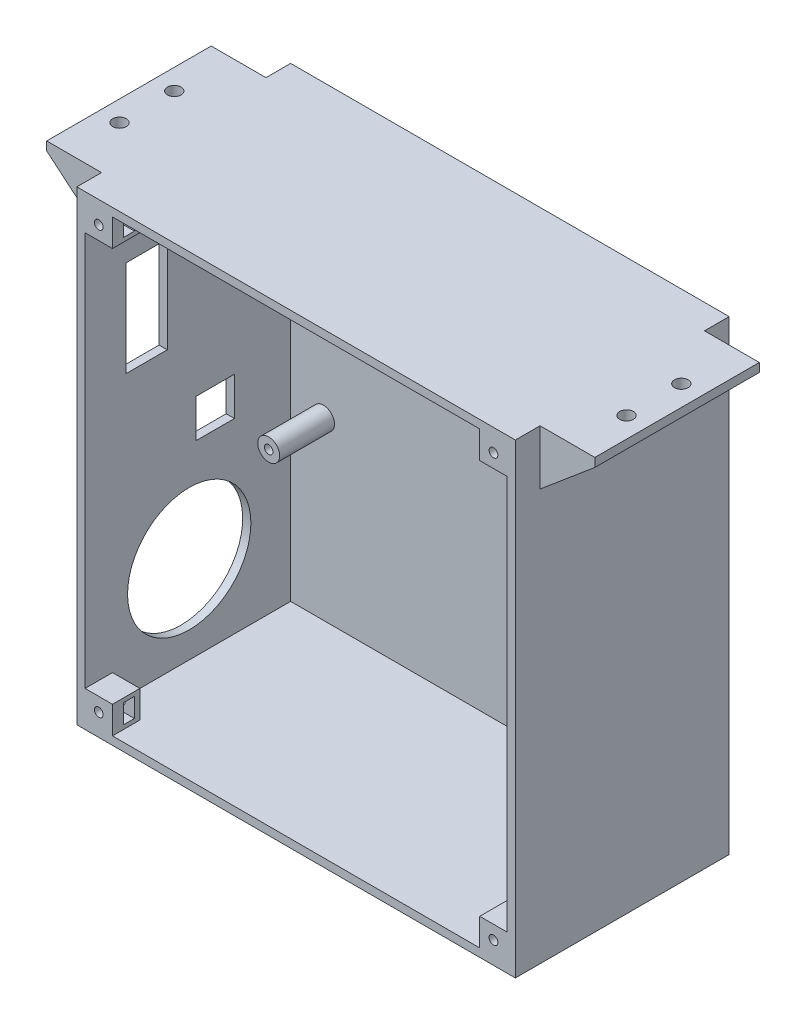
SolidWorks part; units mm, degrees
ref_plane "前视基准面" through (0, 0, 0) normal (0, 0, 1) x (1, 0, 0)
ref_plane "上视基准面" through (0, 0, 0) normal (0, 1, 0) x (1, 0, 0)
ref_plane "右视基准面" through (0, 0, 0) normal (1, 0, 0) x (0, 0, -1)
sketch "草图1" plane through (0, 0, 0) normal (0, 0, 1) x (1, 0, 0)
  line L1 (-27.1147, 8.7287) -> (132.8853, 8.7287)
  line L2 (-27.1147, 8.7287) -> (-27.1147, -161.2713)
  line L3 (-27.1147, -161.2713) -> (132.8853, -161.2713)
  line L4 (132.8853, 8.7287) -> (132.8853, -161.2713)
  dimension "D1" = 160
  dimension "D2" = 170
extrude "凸台-拉伸1" add sketch "草图1" along normal blind 3
sketch "草图9" plane through (0, 0, 3) normal (0, 0, 1) x (1, 0, 0)
  line L1 (-27.1147, 8.7287) -> (132.8853, 8.7287)
  line L2 (-27.1147, 8.7287) -> (-27.1147, -161.2713)
  line L3 (-27.1147, -161.2713) -> (132.8853, -161.2713)
  line L4 (132.8853, 8.7287) -> (132.8853, -161.2713)
  line L5 (-24.1147, 5.7287) -> (129.8853, 5.7287)
  line L6 (-24.1147, 5.7287) -> (-24.1147, -158.2713)
  line L7 (-24.1147, -158.2713) -> (129.8853, -158.2713)
  line L8 (129.8853, 5.7287) -> (129.8853, -158.2713)
  dimension "D1" = 3
  dimension "D2" = 3
  dimension "D3" = 3
  dimension "D4" = 3
extrude "凸台-拉伸6" add sketch "草图9" along normal blind 75
sketch "草图10" plane through (0, 0, 3) normal (0, 0, 1) x (1, 0, 0)
  line L0 (129.8853, 5.7287) -> (-24.1147, 5.7287) construction
  line L1 (-24.1147, 5.7287) -> (-24.1147, -158.2713) construction
  circle A0 centre (-12.1147, -0.2713) radius 4
  circle A1 centre (81.8853, -0.2713) radius 4
  circle A2 centre (-12.1147, -94.2713) radius 4
  circle A3 centre (81.8853, -94.2713) radius 4
  circle A4 centre (-12.1147, -0.2713) radius 1.55
  circle A5 centre (81.8853, -0.2713) radius 1.55
  circle A6 centre (81.8853, -94.2713) radius 1.55
  circle A7 centre (-12.1147, -94.2713) radius 1.55
  dimension "D1" = 8
  dimension "D2" = 8
  dimension "D3" = 8
  dimension "D4" = 8
  dimension "D9" = 94
  dimension "D10" = 3.1
  dimension "D11" = 3.1
  dimension "D12" = 3.1
  dimension "D13" = 3.1
  dimension "D5" = 94
  dimension "D6" = 94
  dimension "D7" = 6
  dimension "D8" = 12
extrude "凸台-拉伸7" add sketch "草图10" along normal blind 20
ref_plane "基准面6" through (0, -92.7213, 0) normal (0, -1, 0) x (-1, 0, 0)
sketch "草图11" plane through (-24.1147, 0, 0) normal (1, 0, 0) x (0, 0, -1)
  line L0 (-23, -90.2713) -> (-23, -98.2713) construction
  line L1 (-37.5, -76.2213) -> (-23.5, -76.2213)
  line L2 (-37.5, -76.2213) -> (-37.5, -90.2213)
  line L3 (-37.5, -90.2213) -> (-23.5, -90.2213)
  line L4 (-23.5, -76.2213) -> (-23.5, -90.2213)
  line L7 (-41.25, -92.7213) -> (41.25, -92.7213) construction
  dimension "D1" = 14
  dimension "D2" = 14
  dimension "D3" = 0.5
  dimension "D4" = 2.5
extrude "切除-拉伸3" cut sketch "草图11" against normal blind 20
sketch "草图12" plane through (-27.1147, 0, 0) normal (-1, 0, 0) x (0, 0, 1)
  line L0 (78, -161.2713) -> (0, -161.2713) construction
  line L1 (0, 8.7287) -> (0, -161.2713) construction
  circle A0 centre (40, -126.2713) radius 22.5
  dimension "D1" = 45
  dimension "D2" = 35
  dimension "D3" = 40
extrude "切除-拉伸4" cut sketch "草图12" against normal blind 10
sketch "草图13" plane through (-27.1147, 0, 0) normal (-1, 0, 0) x (0, 0, 1)
  line L0 (78, 8.7287) -> (0, 8.7287) construction
  line L1 (48, -21.2713) -> (63, -21.2713)
  line L2 (48, -21.2713) -> (48, -56.2713)
  line L3 (48, -56.2713) -> (63, -56.2713)
  line L4 (63, -21.2713) -> (63, -56.2713)
  line L5 (78, 8.7287) -> (78, -161.2713) construction
  dimension "D1" = 15
  dimension "D2" = 35
  dimension "D3" = 30
  dimension "D4" = 15
extrude "切除-拉伸5" cut sketch "草图13" against normal blind 10
ref_plane "基准面7" through (0, -76.2713, 0) normal (0, 1, 0) x (1, 0, 0)
ref_plane "基准面8" through (52.8853, 0, 0) normal (-1, 0, 0) x (0, 0, 1)
sketch "草图14" plane through (0, 5.7287, 0) normal (0, -1, 0) x (1, 0, 0)
  line L1 (-24.1147, 78) -> (-14.1147, 78)
  line L2 (-24.1147, 78) -> (-24.1147, 68)
  line L3 (-24.1147, 68) -> (-14.1147, 68)
  line L4 (-14.1147, 78) -> (-14.1147, 68)
  dimension "D1" = 10
  dimension "D2" = 10
extrude "凸台-拉伸8" add sketch "草图14" along normal blind 10
sketch "草图15" plane through (-14.1147, 0, 0) normal (1, 0, 0) x (0, 0, -1)
  line L0 (-68, -4.2713) -> (-78, -4.2713) construction
  line L1 (-74, 4.2287) -> (-70, 4.2287)
  line L2 (-74, 4.2287) -> (-74, -2.7713)
  line L3 (-74, -2.7713) -> (-70, -2.7713)
  line L4 (-70, 4.2287) -> (-70, -2.7713)
  line L5 (-68, 5.7287) -> (-78, 5.7287) construction
  line L6 (-78, -4.2713) -> (-78, 5.7287) construction
  dimension "D1" = 7
  dimension "D2" = 4
  dimension "D3" = 1.5
  dimension "D4" = 1.5
  dimension "D5" = 4
extrude "切除-拉伸6" cut sketch "草图15" against normal blind 10
sketch "草图16" plane through (0, 0, 78) normal (0, 0, 1) x (1, 0, 0)
  line L0 (-14.1147, -4.2713) -> (-14.1147, 5.7287) construction
  line L1 (-14.1147, -4.2713) -> (-24.1147, -4.2713) construction
  circle A0 centre (-19.1147, 0.7287) radius 1.6
  dimension "D1" = 3.2
  dimension "D2" = 5
  dimension "D3" = 5
extrude "切除-拉伸7" cut sketch "草图16" against normal blind 20
mirror "镜向3" about plane through (52.8853, 0, 0) normal (-1, 0, 0) of "切除-拉伸7", "切除-拉伸6", "凸台-拉伸8"
mirror "镜向4" about plane through (0, -76.2713, 0) normal (0, 1, 0) of "镜向3", "凸台-拉伸8", "切除-拉伸6", "切除-拉伸7"
sketch "草图17" plane through (-27.1147, 0, 0) normal (-1, 0, 0) x (0, 0, 1)
  line L0 (78, 8.7287) -> (0, 8.7287) construction
  line L1 (69, 8.7287) -> (9, 8.7287)
  line L2 (69, 8.7287) -> (69, -11.2713)
  line L3 (69, -11.2713) -> (9, -11.2713)
  line L4 (9, 8.7287) -> (9, -11.2713)
  line L5 (78, 8.7287) -> (78, -161.2713) construction
  line L6 (0, 8.7287) -> (0, -161.2713) construction
  dimension "D1" = 20
  dimension "D2" = 60
  dimension "D3" = 9
  dimension "D4" = 9
extrude "凸台-拉伸9" add sketch "草图17" along normal blind 20
sketch "草图18" plane through (-47.1147, 0, 0) normal (-1, 0, 0) x (0, 0, 1)
  line L0 (9, -11.2713) -> (69, -11.2713) construction
  line L1 (37.45, -11.2713) -> (22.45, -11.2713)
  line L2 (37.45, -11.2713) -> (37.45, 3.7287)
  line L3 (37.45, 3.7287) -> (22.45, 3.7287)
  line L4 (22.45, -11.2713) -> (22.45, 3.7287)
  line L5 (40.0065, 10.2335) -> (40.0066, 14.3494) construction
  line L6 (9, 8.7287) -> (9, -11.2713) construction
  line L7 (19.8812, 212.7292) -> (19.8903, -161.2708) construction
  line L8 (57.45, -11.2713) -> (57.45, 3.7287)
  line L9 (57.45, 3.7287) -> (42.45, 3.7287)
  line L10 (42.45, -11.2713) -> (42.45, 3.7287)
  line L11 (57.45, -11.2713) -> (42.45, -11.2713)
  dimension "D1" = 15
  dimension "D2" = 2.5559
  dimension "D3" = 13.45
  dimension "D4" = 2.5633
  dimension "D5" = 15
  dimension "D6" = 15
  dimension "D7" = 2
extrude "切除-拉伸8" cut sketch "草图18" against normal blind 15
sketch "草图19" plane through (0, 3.7287, 0) normal (0, -1, 0) x (-1, 0, 0)
  line L2 (32.1147, -57.45) -> (32.1147, -42.45) construction
  line L3 (32.1147, -42.45) -> (47.1147, -42.45) construction
  line L4 (32.1147, -37.45) -> (32.1147, -22.45) construction
  line L5 (32.1147, -22.45) -> (47.1147, -22.45) construction
  circle A0 centre (39.6147, -49.95) radius 2.5
  circle A1 centre (39.6147, -29.95) radius 2.5
  point P4 (0, 0)
  point P5 (0, 0)
  point P6 (0, 0)
  dimension "D1" = 5
  dimension "D2" = 5
  dimension "D3" = 7.5
  dimension "D4" = 7.5
  dimension "D5" = 7.5
  dimension "D6" = 7.5
extrude "切除-拉伸9" cut sketch "草图19" against normal blind 15
sketch "草图20" plane through (0, 0, 69) normal (0, 0, 1) x (1, 0, 0)
  line L2 (-47.1147, -11.2713) -> (-27.1147, -11.2713) construction
  line L3 (-47.1147, -11.2713) -> (-27.1147, -11.2713)
  line L5 (-27.1147, -11.2713) -> (-47.1147, 5.558)
  line L6 (-47.1147, 5.558) -> (-47.1147, -11.2713)
extrude "切除-拉伸10" cut sketch "草图20" against normal blind 65
ref_plane "基准面9" through (52.8853, 0, 0) normal (-1, 0, 0) x (0, 0, 1)
mirror "镜向5" about plane through (52.8853, 0, 0) normal (-1, 0, 0) of "切除-拉伸10", "凸台-拉伸9", "切除-拉伸8", "切除-拉伸9"
